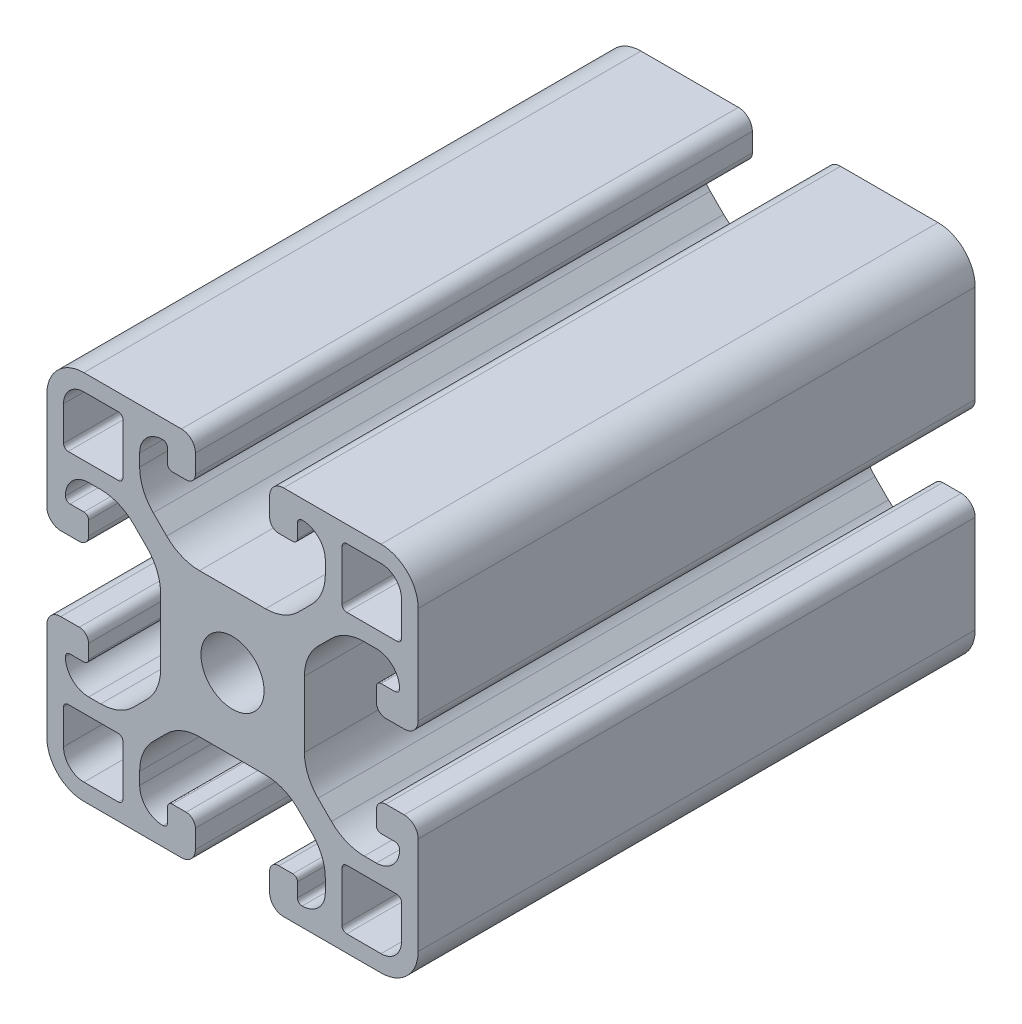
SolidWorks part; units mm, degrees
ref_plane "Plan de face" through (0, 0, 0) normal (0, 0, 1) x (1, 0, 0)
ref_plane "Plan de dessus" through (0, 0, 0) normal (0, 1, 0) x (1, 0, 0)
ref_plane "Plan de droite" through (0, 0, 0) normal (1, 0, 0) x (0, 0, -1)
ref_plane "Plan1" through (0, 0, -30) normal (0, 0, -1) x (-1, 0, 0)
sketch "Esquisse1" plane through (0, 0, -30) normal (0, 0, -1) x (-1, 0, 0)
  line L0 (-4.5, 15) -> (-4.5, 13.5)
  line L1 (-4, 13) -> (-2.5, 13)
  line L2 (-4.5, 10) -> (-5.8076, 10)
  line L3 (-9.3431, 11.4645) -> (-10.7855, 12.9069)
  line L4 (-12.25, 16.4424) -> (-12.25, 23.5576)
  line L5 (-10.7855, 27.0931) -> (-9.3431, 28.5355)
  line L6 (-5.8076, 30) -> (-4.5, 30)
  line L7 (-2.5, 27) -> (-4, 27)
  line L8 (-4.5, 26.5) -> (-4.5, 25)
  line L9 (-3.5, 24) -> (-1.5, 24)
  line L10 (0, 25.5) -> (0, 36)
  line L11 (-4, 40) -> (-14.5, 40)
  line L12 (-16, 38.5) -> (-16, 36.5)
  line L13 (-15, 35.5) -> (-13.5, 35.5)
  line L14 (-13, 36) -> (-13, 37.5)
  line L15 (-10, 35.5) -> (-10, 34.1924)
  line L16 (-11.4645, 30.6569) -> (-12.9069, 29.2145)
  line L17 (-16.4424, 27.75) -> (-23.5576, 27.75)
  line L18 (-27.0931, 29.2145) -> (-28.5355, 30.6569)
  line L19 (-30, 34.1924) -> (-30, 35.5)
  line L20 (-27, 37.5) -> (-27, 36)
  line L21 (-26.5, 35.5) -> (-25, 35.5)
  line L22 (-24, 36.5) -> (-24, 38.5)
  line L23 (-25.5, 40) -> (-36, 40)
  line L24 (-40, 36) -> (-40, 25.5)
  line L25 (-38.5, 24) -> (-36.5, 24)
  line L26 (-35.5, 25) -> (-35.5, 26.5)
  line L27 (-36, 27) -> (-37.5, 27)
  line L28 (-35.5, 30) -> (-34.1924, 30)
  line L29 (-30.6569, 28.5355) -> (-29.2145, 27.0931)
  line L30 (-27.75, 23.5576) -> (-27.75, 16.4424)
  line L31 (-29.2145, 12.9069) -> (-30.6569, 11.4645)
  line L32 (-34.1924, 10) -> (-35.5, 10)
  line L33 (-37.5, 13) -> (-36, 13)
  line L34 (-35.5, 13.5) -> (-35.5, 15)
  line L35 (-36.5, 16) -> (-38.5, 16)
  line L36 (-40, 14.5) -> (-40, 4)
  line L37 (-36, 0) -> (-25.5, 0)
  line L38 (-24, 1.5) -> (-24, 3.5)
  line L39 (-25, 4.5) -> (-26.5, 4.5)
  line L40 (-27, 4) -> (-27, 2.5)
  line L41 (-30, 4.5) -> (-30, 5.8076)
  line L42 (-28.5355, 9.3431) -> (-27.0931, 10.7855)
  line L43 (-23.5576, 12.25) -> (-16.4424, 12.25)
  line L44 (-12.9069, 10.7855) -> (-11.4645, 9.3431)
  line L45 (-10, 5.8076) -> (-10, 4.5)
  line L46 (-13, 2.5) -> (-13, 4)
  line L47 (-13.5, 4.5) -> (-15, 4.5)
  line L48 (-16, 3.5) -> (-16, 1.5)
  line L49 (-14.5, 0) -> (-4, 0)
  line L50 (0, 4) -> (0, 14.5)
  line L51 (-1.5, 16) -> (-3.5, 16)
  line L52 (-4, 1.8) -> (-7.7, 1.8)
  line L53 (-8.2, 2.3) -> (-8.2, 7.7)
  line L54 (-7.7, 8.2) -> (-2.3, 8.2)
  line L55 (-1.8, 7.7) -> (-1.8, 4)
  line L56 (-38.2, 4) -> (-38.2, 7.7)
  line L57 (-37.7, 8.2) -> (-32.3, 8.2)
  line L58 (-31.8, 7.7) -> (-31.8, 2.3)
  line L59 (-32.3, 1.8) -> (-36, 1.8)
  line L60 (-36, 38.2) -> (-32.3, 38.2)
  line L61 (-31.8, 37.7) -> (-31.8, 32.3)
  line L62 (-32.3, 31.8) -> (-37.7, 31.8)
  line L63 (-38.2, 32.3) -> (-38.2, 36)
  line L64 (-1.8, 36) -> (-1.8, 32.3)
  line L65 (-2.3, 31.8) -> (-7.7, 31.8)
  line L66 (-8.2, 32.3) -> (-8.2, 37.7)
  line L67 (-7.7, 38.2) -> (-4, 38.2)
  arc A0 (-4.5, 13.5) -> (-4, 13) centre (-4, 13.5) ccw
  arc A1 (-2.5, 13) -> (-2, 12.5) centre (-2.5, 12.5) cw
  arc A2 (-2, 12.5) -> (-4.5, 10) centre (-4.5, 12.5) cw
  arc A3 (-5.8076, 10) -> (-9.3431, 11.4645) centre (-5.8076, 15) cw
  arc A4 (-10.7855, 12.9069) -> (-12.25, 16.4424) centre (-7.25, 16.4424) cw
  arc A5 (-12.25, 23.5576) -> (-10.7855, 27.0931) centre (-7.25, 23.5576) cw
  arc A6 (-9.3431, 28.5355) -> (-5.8076, 30) centre (-5.8076, 25) cw
  arc A7 (-4.5, 30) -> (-2, 27.5) centre (-4.5, 27.5) cw
  arc A8 (-2, 27.5) -> (-2.5, 27) centre (-2.5, 27.5) cw
  arc A9 (-4, 27) -> (-4.5, 26.5) centre (-4, 26.5) ccw
  arc A10 (-4.5, 25) -> (-3.5, 24) centre (-3.5, 25) ccw
  arc A11 (-1.5, 24) -> (0, 25.5) centre (-1.5, 25.5) ccw
  arc A12 (0, 36) -> (-4, 40) centre (-4, 36) ccw
  arc A13 (-14.5, 40) -> (-16, 38.5) centre (-14.5, 38.5) ccw
  arc A14 (-16, 36.5) -> (-15, 35.5) centre (-15, 36.5) ccw
  arc A15 (-13.5, 35.5) -> (-13, 36) centre (-13.5, 36) ccw
  arc A16 (-13, 37.5) -> (-12.5, 38) centre (-12.5, 37.5) cw
  arc A17 (-12.5, 38) -> (-10, 35.5) centre (-12.5, 35.5) cw
  arc A18 (-10, 34.1924) -> (-11.4645, 30.6569) centre (-15, 34.1924) cw
  arc A19 (-12.9069, 29.2145) -> (-16.4424, 27.75) centre (-16.4424, 32.75) cw
  arc A20 (-23.5576, 27.75) -> (-27.0931, 29.2145) centre (-23.5576, 32.75) cw
  arc A21 (-28.5355, 30.6569) -> (-30, 34.1924) centre (-25, 34.1924) cw
  arc A22 (-30, 35.5) -> (-27.5, 38) centre (-27.5, 35.5) cw
  arc A23 (-27.5, 38) -> (-27, 37.5) centre (-27.5, 37.5) cw
  arc A24 (-27, 36) -> (-26.5, 35.5) centre (-26.5, 36) ccw
  arc A25 (-25, 35.5) -> (-24, 36.5) centre (-25, 36.5) ccw
  arc A26 (-24, 38.5) -> (-25.5, 40) centre (-25.5, 38.5) ccw
  arc A27 (-36, 40) -> (-40, 36) centre (-36, 36) ccw
  arc A28 (-40, 25.5) -> (-38.5, 24) centre (-38.5, 25.5) ccw
  arc A29 (-36.5, 24) -> (-35.5, 25) centre (-36.5, 25) ccw
  arc A30 (-35.5, 26.5) -> (-36, 27) centre (-36, 26.5) ccw
  arc A31 (-37.5, 27) -> (-38, 27.5) centre (-37.5, 27.5) cw
  arc A32 (-38, 27.5) -> (-35.5, 30) centre (-35.5, 27.5) cw
  arc A33 (-34.1924, 30) -> (-30.6569, 28.5355) centre (-34.1924, 25) cw
  arc A34 (-29.2145, 27.0931) -> (-27.75, 23.5576) centre (-32.75, 23.5576) cw
  arc A35 (-27.75, 16.4424) -> (-29.2145, 12.9069) centre (-32.75, 16.4424) cw
  arc A36 (-30.6569, 11.4645) -> (-34.1924, 10) centre (-34.1924, 15) cw
  arc A37 (-35.5, 10) -> (-38, 12.5) centre (-35.5, 12.5) cw
  arc A38 (-38, 12.5) -> (-37.5, 13) centre (-37.5, 12.5) cw
  arc A39 (-36, 13) -> (-35.5, 13.5) centre (-36, 13.5) ccw
  arc A40 (-35.5, 15) -> (-36.5, 16) centre (-36.5, 15) ccw
  arc A41 (-38.5, 16) -> (-40, 14.5) centre (-38.5, 14.5) ccw
  arc A42 (-40, 4) -> (-36, 0) centre (-36, 4) ccw
  arc A43 (-25.5, 0) -> (-24, 1.5) centre (-25.5, 1.5) ccw
  arc A44 (-24, 3.5) -> (-25, 4.5) centre (-25, 3.5) ccw
  arc A45 (-26.5, 4.5) -> (-27, 4) centre (-26.5, 4) ccw
  arc A46 (-27, 2.5) -> (-27.5, 2) centre (-27.5, 2.5) cw
  arc A47 (-27.5, 2) -> (-30, 4.5) centre (-27.5, 4.5) cw
  arc A48 (-30, 5.8076) -> (-28.5355, 9.3431) centre (-25, 5.8076) cw
  arc A49 (-27.0931, 10.7855) -> (-23.5576, 12.25) centre (-23.5576, 7.25) cw
  arc A50 (-16.4424, 12.25) -> (-12.9069, 10.7855) centre (-16.4424, 7.25) cw
  arc A51 (-11.4645, 9.3431) -> (-10, 5.8076) centre (-15, 5.8076) cw
  arc A52 (-10, 4.5) -> (-12.5, 2) centre (-12.5, 4.5) cw
  arc A53 (-12.5, 2) -> (-13, 2.5) centre (-12.5, 2.5) cw
  arc A54 (-13, 4) -> (-13.5, 4.5) centre (-13.5, 4) ccw
  arc A55 (-15, 4.5) -> (-16, 3.5) centre (-15, 3.5) ccw
  arc A56 (-16, 1.5) -> (-14.5, 0) centre (-14.5, 1.5) ccw
  arc A57 (-4, 0) -> (0, 4) centre (-4, 4) ccw
  arc A58 (0, 14.5) -> (-1.5, 16) centre (-1.5, 14.5) ccw
  arc A59 (-3.5, 16) -> (-4.5, 15) centre (-3.5, 15) ccw
  circle A60 centre (-20, 20) radius 3.4
  arc A61 (-1.8, 4) -> (-4, 1.8) centre (-4, 4) cw
  arc A62 (-7.7, 1.8) -> (-8.2, 2.3) centre (-7.7, 2.3) cw
  arc A63 (-8.2, 7.7) -> (-7.7, 8.2) centre (-7.7, 7.7) cw
  arc A64 (-2.3, 8.2) -> (-1.8, 7.7) centre (-2.3, 7.7) cw
  arc A65 (-36, 1.8) -> (-38.2, 4) centre (-36, 4) cw
  arc A66 (-38.2, 7.7) -> (-37.7, 8.2) centre (-37.7, 7.7) cw
  arc A67 (-32.3, 8.2) -> (-31.8, 7.7) centre (-32.3, 7.7) cw
  arc A68 (-31.8, 2.3) -> (-32.3, 1.8) centre (-32.3, 2.3) cw
  arc A69 (-38.2, 36) -> (-36, 38.2) centre (-36, 36) cw
  arc A70 (-32.3, 38.2) -> (-31.8, 37.7) centre (-32.3, 37.7) cw
  arc A71 (-31.8, 32.3) -> (-32.3, 31.8) centre (-32.3, 32.3) cw
  arc A72 (-37.7, 31.8) -> (-38.2, 32.3) centre (-37.7, 32.3) cw
  arc A73 (-4, 38.2) -> (-1.8, 36) centre (-4, 36) cw
  arc A74 (-1.8, 32.3) -> (-2.3, 31.8) centre (-2.3, 32.3) cw
  arc A75 (-7.7, 31.8) -> (-8.2, 32.3) centre (-7.7, 32.3) cw
  arc A76 (-8.2, 37.7) -> (-7.7, 38.2) centre (-7.7, 37.7) cw
extrude "Boss.-Extru.1" add sketch "Esquisse1" against normal blind 60
